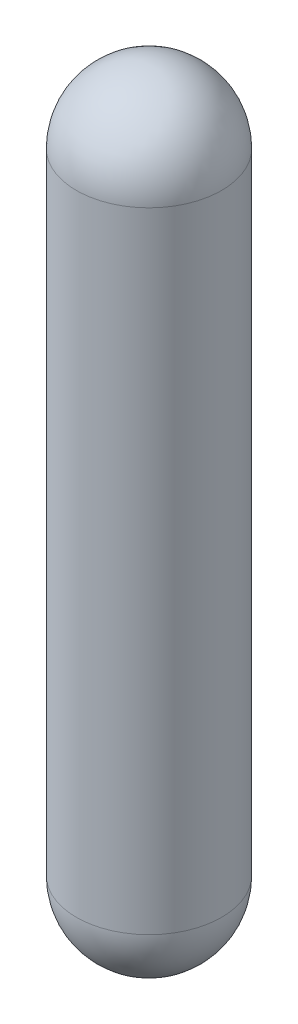
SolidWorks part; units mm, degrees
ref_plane "Plan de face" through (0, 0, 0) normal (0, 0, 1) x (1, 0, 0)
ref_plane "Plan de dessus" through (0, 0, 0) normal (0, 1, 0) x (1, 0, 0)
ref_plane "Plan de droite" through (0, 0, 0) normal (1, 0, 0) x (0, 0, -1)
sketch "Esquisse1" plane through (0, 0, 0) normal (0, 0, 1) x (1, 0, 0)
  line L0 (-3, 29) -> (-3, 3)
  line L5 (0, 0) -> (0, 110.3002) construction
  line L6 (0, 32) -> (0, 0)
  arc A0 (-3, 29) -> (0, 32) centre (0, 29) cw
  arc A1 (-3, 3) -> (0, 0) centre (0, 3) ccw
  dimension "D1" = 3
  dimension "D2" = 3
  dimension "D3" = 32
revolve "Révolution1" add sketch "Esquisse1" angle 360 about L5
